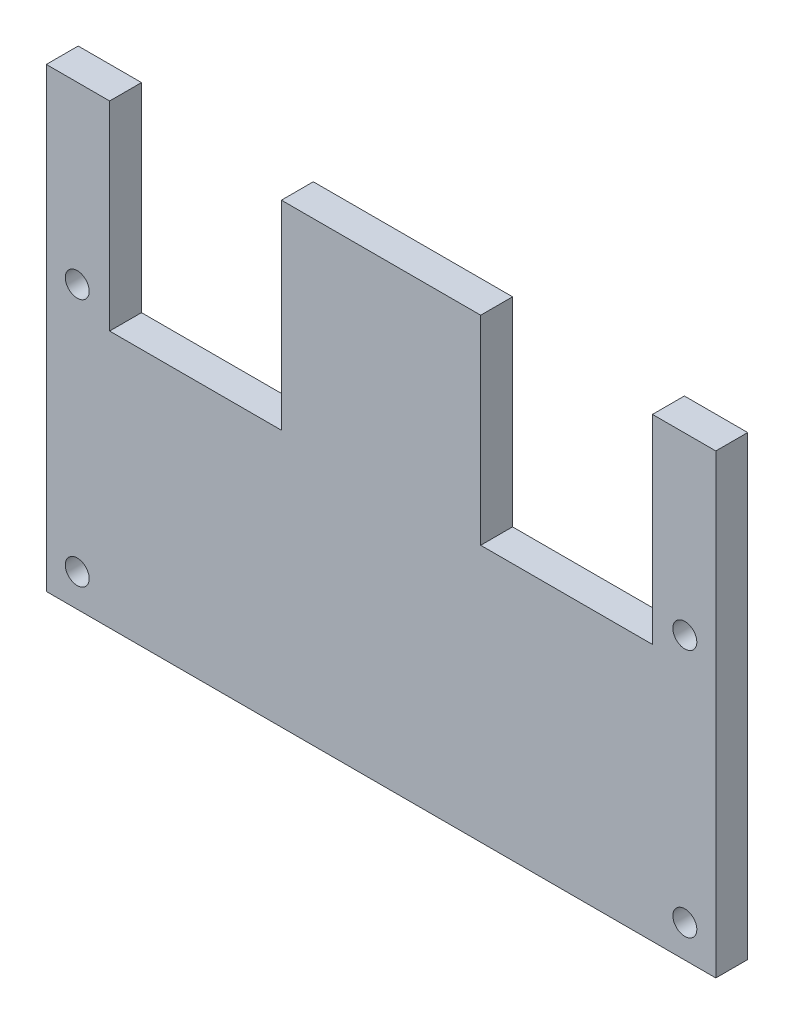
SolidWorks part; units mm, degrees
ref_plane "前视基准面" through (0, 0, 0) normal (0, 0, 1) x (1, 0, 0)
ref_plane "上视基准面" through (0, 0, 0) normal (0, 1, 0) x (1, 0, 0)
ref_plane "右视基准面" through (0, 0, 0) normal (1, 0, 0) x (0, 0, -1)
other "Configuration Table"
sketch "草图1" plane through (0, 0, 0) normal (0, 0, 1) x (1, 0, 0)
  line L0 (-0.4899, 0) -> (0.5421, 0) construction
  line L1 (-0.1364, 1115.663) -> (-0.1364, 57.2692) construction
  line L2 (-42.1364, 0) -> (41.8636, 0)
  line L5 (-34.1914, 32.2692) -> (-34.1914, 57.2692)
  line L6 (-34.1914, 57.2692) -> (-42.1364, 57.2692)
  line L7 (-42.1364, 57.2692) -> (-42.1364, 0)
  line L9 (33.9186, 32.2692) -> (33.9186, 57.2692)
  line L10 (33.9186, 57.2692) -> (41.8636, 57.2692)
  line L11 (41.8636, 57.2692) -> (41.8636, 0)
  line L12 (-0.1364, 0) -> (-0.1364, -1001.0967) construction
  line L14 (-12.6364, 32.2692) -> (-12.6364, 57.2692)
  line L15 (-12.6364, 57.2692) -> (12.3636, 57.2692)
  line L16 (12.3636, 32.2692) -> (12.3636, 57.2692)
  line L17 (-34.1914, 32.2692) -> (-12.6364, 32.2692)
  line L19 (12.3636, 32.2692) -> (33.9186, 32.2692)
  dimension "D4" = 7.945
  dimension "D5" = 25
extrude "凸台-拉伸1" add sketch "草图1" along normal blind 4 contours L15 L16 L19 L9 L10 L11 L2 L7 L6 L5 L17 L14
sketch "草图7" plane through (0, 0, 4) normal (0, 0, 1) x (1, 0, 0)
  line L0 (-0.1364, 0) -> (-0.1364, 50000) construction
  line L1 (-42.1364, 0) -> (41.8636, 0) construction
  circle A0 centre (-38.2537, 4.0779) radius 1.5
  circle A3 centre (-38.2537, 35.306) radius 1.5
  circle A4 centre (37.9809, 35.306) radius 1.5
  circle A5 centre (37.9809, 4.0779) radius 1.5
  point P7 (-0.1364, 0)
  point P9 (-38.2537, 35.306)
extrude "切除-拉伸1" cut sketch "草图7" against normal through all both and the other way through all
